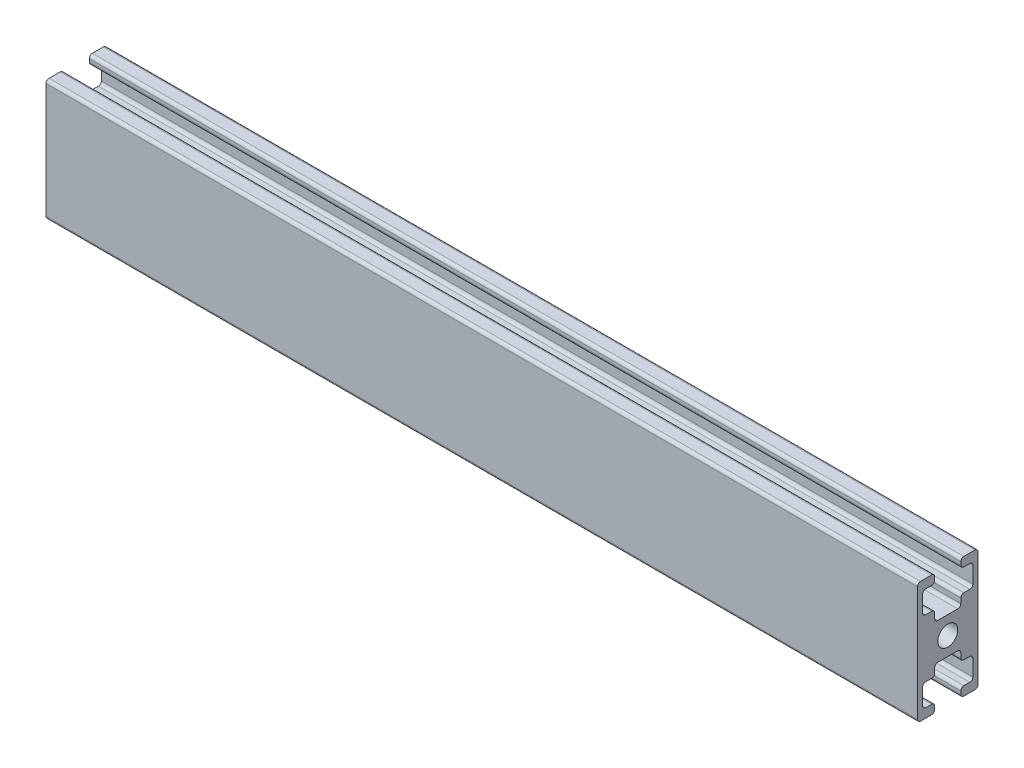
SolidWorks part; units mm, degrees
ref_plane "正面" through (0, 0, 0) normal (0, 0, 1) x (1, 0, 0)
ref_plane "平面" through (0, 0, 0) normal (0, 1, 0) x (1, 0, 0)
ref_plane "右側面" through (0, 0, 0) normal (1, 0, 0) x (0, 0, -1)
sketch "ｽｹｯﾁ1" plane through (0, 0, 0) normal (1, 0, 0) x (0, 0, -1)
  line L0 (0.5, 0) -> (2.35, 0)
  line L1 (2.85, 0.5) -> (2.85, 1)
  line L2 (0, 0.5) -> (0, 19.5)
  line L3 (2.35, 1.5) -> (1.35, 1.5)
  line L4 (0.85, 2) -> (0.85, 4.7)
  line L5 (1.35, 5.2) -> (2.35, 5.2)
  line L6 (2.85, 5.7) -> (2.85, 6.5)
  line L7 (3.35, 7) -> (6.65, 7)
  line L8 (5, 10) -> (5, -2.4578) construction
  line L9 (5, 10) -> (12.3012, 10) construction
  line L10 (7.15, 5.7) -> (7.15, 6.5)
  line L11 (8.65, 5.2) -> (7.65, 5.2)
  line L12 (9.15, 2) -> (9.15, 4.7)
  line L13 (7.65, 1.5) -> (8.65, 1.5)
  line L14 (10, 0.5) -> (10, 19.5)
  line L15 (7.15, 0.5) -> (7.15, 1)
  line L16 (9.5, 0) -> (7.65, 0)
  line L17 (9.5, 20) -> (7.65, 20)
  line L18 (7.15, 19.5) -> (7.15, 19)
  line L19 (7.65, 18.5) -> (8.65, 18.5)
  line L20 (9.15, 18) -> (9.15, 15.3)
  line L21 (8.65, 14.8) -> (7.65, 14.8)
  line L22 (7.15, 14.3) -> (7.15, 13.5)
  line L23 (3.35, 13) -> (6.65, 13)
  line L24 (2.85, 14.3) -> (2.85, 13.5)
  line L25 (1.35, 14.8) -> (2.35, 14.8)
  line L26 (0.85, 18) -> (0.85, 15.3)
  line L27 (2.35, 18.5) -> (1.35, 18.5)
  line L28 (2.85, 19.5) -> (2.85, 19)
  line L29 (0.5, 20) -> (2.35, 20)
  circle A0 centre (5, 10) radius 1.65
  arc A1 (2.85, 6.5) -> (3.35, 7) centre (3.35, 6.5) cw
  arc A2 (2.35, 5.2) -> (2.85, 5.7) centre (2.35, 5.7) ccw
  arc A3 (0.85, 4.7) -> (1.35, 5.2) centre (1.35, 4.7) cw
  arc A4 (0.5, 0) -> (0, 0.5) centre (0.5, 0.5) cw
  arc A5 (2.35, 0) -> (2.85, 0.5) centre (2.35, 0.5) ccw
  arc A6 (2.85, 1) -> (2.35, 1.5) centre (2.35, 1) ccw
  arc A7 (1.35, 1.5) -> (0.85, 2) centre (1.35, 2) cw
  arc A8 (8.65, 1.5) -> (9.15, 2) centre (8.65, 2) ccw
  arc A9 (7.15, 1) -> (7.65, 1.5) centre (7.65, 1) cw
  arc A10 (7.65, 0) -> (7.15, 0.5) centre (7.65, 0.5) cw
  arc A11 (9.5, 0) -> (10, 0.5) centre (9.5, 0.5) ccw
  arc A12 (9.15, 4.7) -> (8.65, 5.2) centre (8.65, 4.7) ccw
  arc A13 (7.65, 5.2) -> (7.15, 5.7) centre (7.65, 5.7) cw
  arc A14 (7.15, 6.5) -> (6.65, 7) centre (6.65, 6.5) ccw
  arc A15 (7.15, 13.5) -> (6.65, 13) centre (6.65, 13.5) cw
  arc A16 (7.65, 14.8) -> (7.15, 14.3) centre (7.65, 14.3) ccw
  arc A17 (9.15, 15.3) -> (8.65, 14.8) centre (8.65, 15.3) cw
  arc A18 (9.5, 20) -> (10, 19.5) centre (9.5, 19.5) cw
  arc A19 (7.65, 20) -> (7.15, 19.5) centre (7.65, 19.5) ccw
  arc A20 (7.15, 19) -> (7.65, 18.5) centre (7.65, 19) ccw
  arc A21 (8.65, 18.5) -> (9.15, 18) centre (8.65, 18) cw
  arc A22 (1.35, 18.5) -> (0.85, 18) centre (1.35, 18) ccw
  arc A23 (2.85, 19) -> (2.35, 18.5) centre (2.35, 19) cw
  arc A24 (2.35, 20) -> (2.85, 19.5) centre (2.35, 19.5) cw
  arc A25 (0.5, 20) -> (0, 19.5) centre (0.5, 19.5) ccw
  arc A26 (0.85, 15.3) -> (1.35, 14.8) centre (1.35, 15.3) ccw
  arc A27 (2.35, 14.8) -> (2.85, 14.3) centre (2.35, 14.3) cw
  arc A28 (2.85, 13.5) -> (3.35, 13) centre (3.35, 13.5) ccw
  point P1 (7.15, 13)
  point P12 (0, 10)
  point P17 (5, 7)
  point P39 (2.85, 7)
  point P42 (2.85, 5.2)
  point P45 (0.85, 5.2)
  point P48 (0, 0)
  point P51 (2.85, 0)
  point P54 (2.85, 1.5)
  point P57 (0.85, 1.5)
  point P59 (5, 7)
  point P60 (9.15, 1.5)
  point P61 (7.15, 1.5)
  point P62 (7.15, 0)
  point P63 (10, 0)
  point P64 (9.15, 5.2)
  point P65 (7.15, 5.2)
  point P66 (7.15, 7)
  point P109 (10, 10)
  point P110 (7.15, 14.8)
  point P111 (9.15, 14.8)
  point P112 (10, 20)
  point P113 (7.15, 20)
  point P114 (7.15, 18.5)
  point P115 (9.15, 18.5)
  point P116 (5, 13)
  point P117 (0.85, 18.5)
  point P118 (2.85, 18.5)
  point P119 (2.85, 20)
  point P120 (0, 20)
  point P121 (0.85, 14.8)
  point P122 (2.85, 14.8)
  point P123 (2.85, 13)
  dimension "D1" = 0.5
extrude "ﾎﾞｽ - 押し出し1" add sketch "ｽｹｯﾁ1" along normal blind 144
